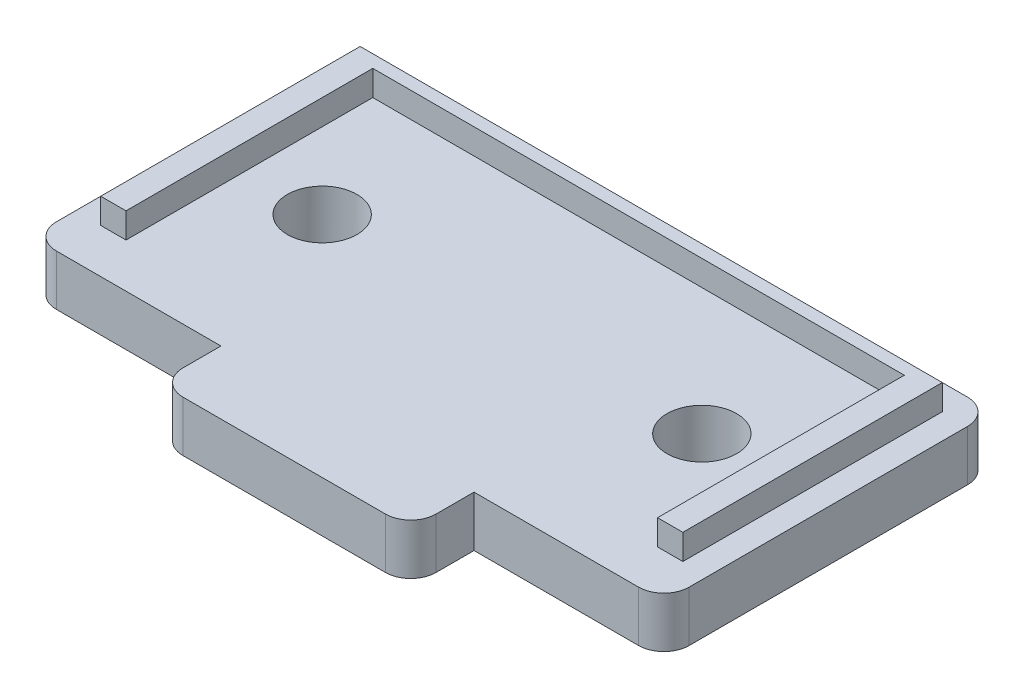
SolidWorks part; units mm, degrees
ref_plane "前视基准面" through (0, 0, 0) normal (0, 0, 1) x (1, 0, 0)
ref_plane "上视基准面" through (0, 0, 0) normal (0, 1, 0) x (1, 0, 0)
ref_plane "右视基准面" through (0, 0, 0) normal (1, 0, 0) x (0, 0, -1)
other "Configuration Table"
sketch "草图1" plane through (0, 0, 0) normal (0, 1, 0) x (1, 0, 0)
  line L0 (0, -18) -> (0, -4.3213) construction
  line L1 (-25, 13) -> (25, 13)
  line L2 (-25, 13) -> (-25, -13)
  line L3 (-25, -13) -> (-10, -13)
  line L4 (25, 13) -> (25, -13)
  line L5 (-25, 13) -> (25, -13) construction
  line L6 (-25, -13) -> (25, 13) construction
  line L8 (-10, -13) -> (-10, -18)
  line L9 (-10, -18) -> (10, -18)
  line L10 (10, -13) -> (10, -18)
  line L11 (10, -13) -> (25, -13)
  point P0 (0, 0)
  dimension "D1" = 26
  dimension "D2" = 50
  dimension "D3" = 20
  dimension "D4" = 5
extrude "凸台-拉伸1" add sketch "草图1" along normal blind 4
fillet "圆角1" radius 2 6 edges at (-25, 2, -13) (25, 2, -13) (-25, 2, 13) (-10, 2, 18) (10, 2, 18) (25, 2, 13)
sketch "草图3" plane through (0, 4, 0) normal (0, 1, 0) x (1, 0, 0)
  line L0 (0, 0) -> (0, 16.0816) construction
  circle A0 centre (-15, 0) radius 2.75
  circle A1 centre (15, 0) radius 2.75
  dimension "D1" = 5.5
  dimension "D2" = 30
extrude "切除-拉伸1" cut sketch "草图3" against normal up to next
sketch "草图4" plane through (0, 4, 0) normal (0, 1, 0) x (1, 0, 0)
  line L0 (21, -9.5) -> (21, 9.5) construction
  line L1 (-21, 9.5) -> (-21, -9.5) construction
  line L2 (-20.5, 10) -> (-8.5, 10) construction
  line L3 (21, -9.5) -> (21, 9.5)
  line L4 (-21, 9.5) -> (-21, -9.5)
  line L5 (-20.5, 10) -> (-8.5, 10)
  line L6 (-20.5, 10) -> (-21, 10)
  line L7 (-21, 10) -> (-21, 9.5)
  line L24 (-8.5, 10) -> (21, 10)
  line L25 (21, 10) -> (21, 9.5)
  line L26 (-23, -9.5) -> (-23, 11)
  line L27 (-23, 11) -> (23, 11)
  line L28 (23, 11) -> (23, -9.5)
  line L29 (23, -9.5) -> (21, -9.5)
  line L30 (-21, -9.5) -> (-23, -9.5)
extrude "凸台-拉伸2" add sketch "草图4" along normal blind 2
